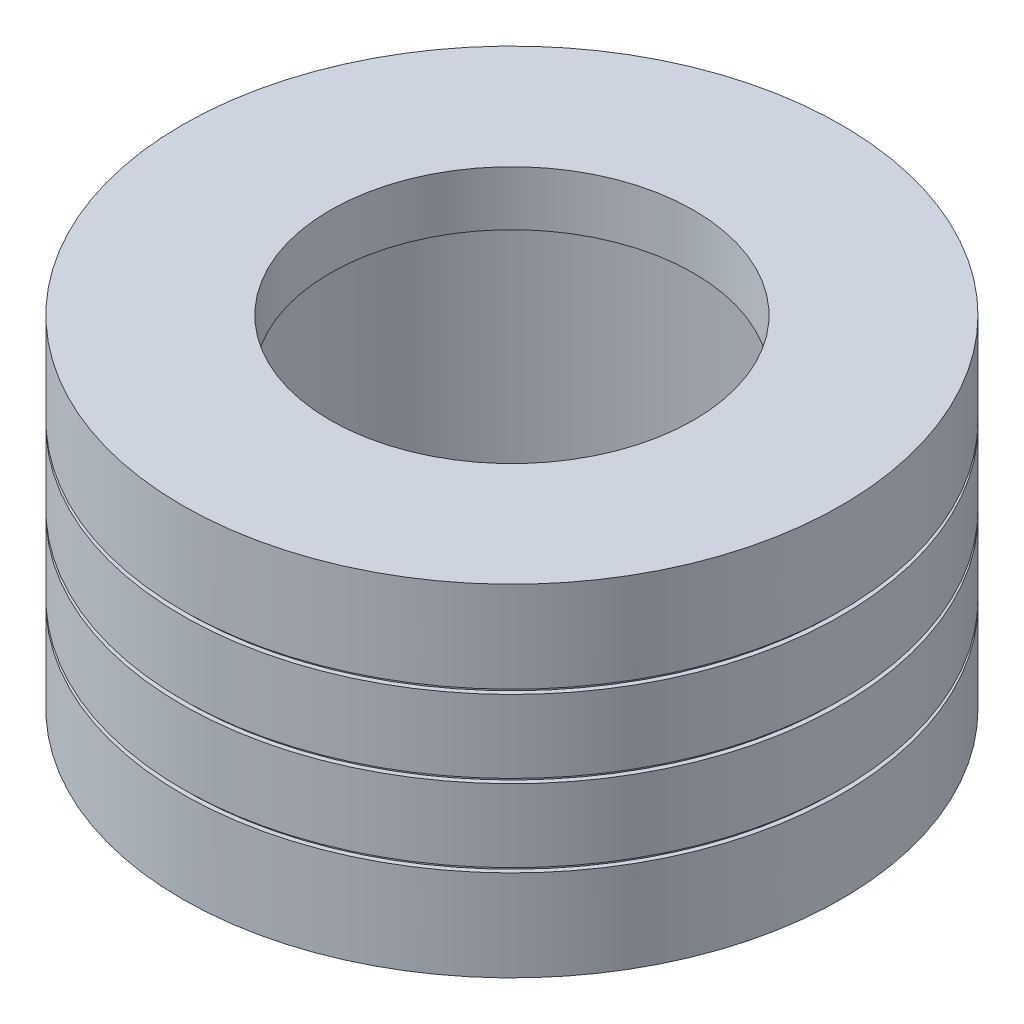
SolidWorks part; units mm, degrees
material "5052-H34"
ref_plane "正面" through (0, 0, 0) normal (0, 0, 1) x (1, 0, 0)
ref_plane "平面" through (0, 0, 0) normal (0, 1, 0) x (1, 0, 0)
ref_plane "右側面" through (0, 0, 0) normal (1, 0, 0) x (0, 0, -1)
sketch "ｽｹｯﾁ1" plane through (0, 0, 0) normal (0, 1, 0) x (1, 0, 0)
  circle A0 centre (0, 0) radius 7.25
  dimension "D1" = 14.5
extrude "ﾎﾞｽ - 押し出し1" add sketch "ｽｹｯﾁ1" along normal blind 7.5
sketch "ｽｹｯﾁ2" plane through (0, 0, 0) normal (0, -1, 0) x (1, 0, 0)
  circle A0 centre (0, 0) radius 6.4
  dimension "D1" = 12.8
extrude "ｶｯﾄ - 押し出し1" cut sketch "ｽｹｯﾁ2" against normal blind 6.3
sketch "ｽｹｯﾁ4" plane through (0, 7.5, 0) normal (0, 1, 0) x (1, 0, 0)
  circle A0 centre (0, 0) radius 4
  dimension "D1" = 8
extrude "ｶｯﾄ - 押し出し2" cut sketch "ｽｹｯﾁ4" against normal up to surface (1.2 mm away) up to face at (0, 6.3, -6.4)
sketch "ｽｹｯﾁ3" plane through (0, 0, 0) normal (0, 0, 1) x (1, 0, 0)
  line L0 (0, 7.5) -> (0, 0) construction
  line L1 (7.25, 7.5) -> (-7.25, 7.5) construction
  line L2 (-7.25, 7.5) -> (-7.25, 0) construction
  line L3 (-7.25, 5.5) -> (-7.15, 5.5)
  line L4 (-7.25, 5.5) -> (-7.25, 5.4)
  line L5 (-7.25, 5.4) -> (-7.15, 5.4)
  line L6 (-7.15, 5.5) -> (-7.15, 5.4)
  line L7 (-7.25, 3.8) -> (-7.15, 3.8)
  line L8 (-7.25, 3.8) -> (-7.25, 3.7)
  line L9 (-7.25, 3.7) -> (-7.15, 3.7)
  line L10 (-7.15, 3.8) -> (-7.15, 3.7)
  line L11 (-7.25, 2.1) -> (-7.15, 2.1)
  line L12 (-7.25, 2.1) -> (-7.25, 2)
  line L13 (-7.25, 2) -> (-7.15, 2)
  line L14 (-7.15, 2.1) -> (-7.15, 2)
  line L15 (-7.25, 0) -> (7.25, 0) construction
  dimension "D1" = 0.1
  dimension "D2" = 0.1
  dimension "D3" = 2
  dimension "D5" = 2
  dimension "D4" = 3
revolve "ｶｯﾄ - 回転1" cut sketch "ｽｹｯﾁ3" angle 360 about L0
